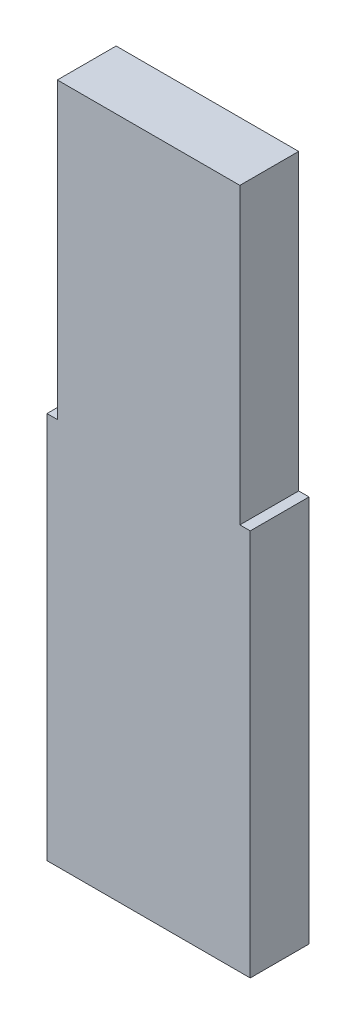
SolidWorks part; units mm, degrees
material "Plain Carbon Steel"
ref_plane "Front Plane" through (0, 0, 0) normal (0, 0, 1) x (1, 0, 0)
ref_plane "Top Plane" through (0, 0, 0) normal (0, 1, 0) x (1, 0, 0)
ref_plane "Right Plane" through (0, 0, 0) normal (1, 0, 0) x (0, 0, -1)
sketch "Sketch1" plane through (0, 0, 0) normal (0, 0, 1) x (1, 0, 0)
  line B0 (50.6598, -22.4809) -> (50.6598, -6.6059)
  line B1 (40.8052, -6.6059) -> (40.8052, -22.4809)
  line B2 (-11.4373, 39.0502) -> (-4.7473, 45.8293)
  line B3 (-4.7473, 45.8293) -> (-4.9808, 47.592)
  line B4 (-4.9808, 47.592) -> (-15.3046, 46.2245)
  line B5 (-15.3046, 46.2245) -> (-8.7339, -3.3803)
  line B6 (1.7621, -11.47) -> (46.5302, -5.8079)
  line B7 (45.5334, 6.8529) -> (5.0154, 5.583)
  line B8 (0.0223, 9.8219) -> (-2.4793, 28.7069)
  line B9 (-2.4793, 28.7069) -> (-10.7035, 33.5105)
  line B10 (-4.7473, 45.8293) -> (-2.4793, 28.7069)
  line B11 (-2.4793, 28.7069) -> (-0.2634, 29.0004)
  line B12 (-0.2634, 29.0004) -> (-2.1979, 43.6049)
  line B13 (-2.1979, 43.6049) -> (1.8812, 44.1452)
  line B14 (1.8812, 44.1452) -> (1.5477, 46.6632)
  line B15 (1.5477, 46.6632) -> (-4.7473, 45.8293)
  line B16 (55.1305, -12.1939) -> (51.9321, 1.9053)
  line B17 (46.5302, -5.8079) -> (37.5248, -6.9469)
  line B18 (37.5248, -6.9469) -> (36.3345, -12.1939)
  line B19 (36.3345, -12.1939) -> (39.3825, -12.1939)
  line B20 (52.0825, -12.1939) -> (55.1305, -12.1939)
  line B21 (51.2189, -43.3851) -> (40.2461, -43.3851)
  line B22 (51.2189, -43.3851) -> (51.2189, -22.4809)
  line B23 (40.2461, -22.4809) -> (40.2461, -43.3851)
  line B24 (40.8052, -22.4809) -> (40.2461, -22.4809)
  circle B25 centre (0, 0) radius 6.35
  arc B26 (-11.4373, 39.0502) -> (-10.7035, 33.5105) centre (-8.9193, 36.5653) ccw
  arc B27 (-8.7339, -3.3803) -> (1.7621, -11.47) centre (0.5828, -2.1462) ccw
  arc B28 (46.5302, -5.8079) -> (45.5334, 6.8529) centre (45.7325, 0.499) ccw
  arc B29 (0.0223, 9.8219) -> (5.0154, 5.583) centre (4.8624, 10.463) ccw
  arc B30 (39.3825, -12.1939) -> (52.0825, -12.1939) centre (45.7325, -12.1939) ccw
sketch_block_instance "Cam Geometry-1"
sketch_block "Cam Geometry"
sketch "Sketch2" plane through (0, 0, 0) normal (0, 0, 1) x (1, 0, 0)
  line L28 (40.8052, -6.6059) -> (50.6598, -6.6059)
  line L30 (50.6598, -6.6059) -> (50.6598, -22.4809)
  line L31 (50.6598, -22.4809) -> (51.2189, -22.4809)
  line L32 (51.2189, -22.4809) -> (51.2189, -43.3851)
  line L33 (51.2189, -43.3851) -> (40.2461, -43.3851)
  line L34 (40.2461, -43.3851) -> (40.2461, -22.4809)
  line L35 (40.2461, -22.4809) -> (40.8052, -22.4809)
  line L36 (40.8052, -22.4809) -> (40.8052, -6.6059)
extrude "Boss-Extrude1" add sketch "Sketch2" along normal mid plane 3.175
ref_plane "Plane1" through (45.7325, 0, 0) normal (-1, 0, 0) x (0, 0, 1)
